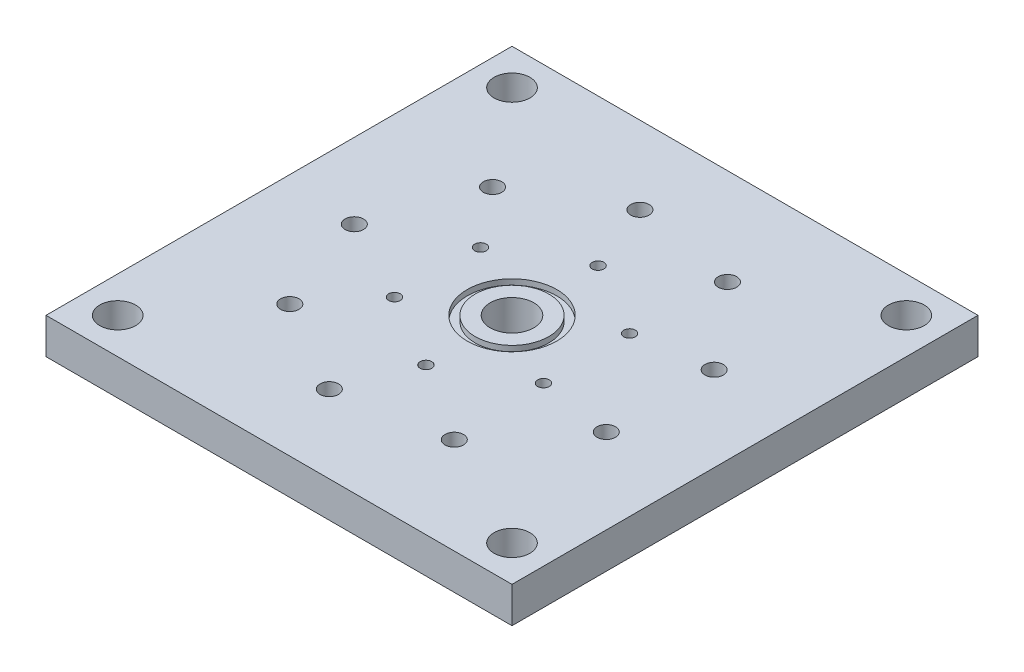
SolidWorks part; units mm, degrees
ref_plane "Front Plane" through (0, 0, 0) normal (0, 0, 1) x (1, 0, 0)
ref_plane "Top Plane" through (0, 0, 0) normal (0, 1, 0) x (1, 0, 0)
ref_plane "Right Plane" through (0, 0, 0) normal (1, 0, 0) x (0, 0, -1)
sketch "Sketch1" plane through (0, 0, 0) normal (0, 1, 0) x (1, 0, 0)
  line L1 (-41.275, -41.275) -> (41.275, -41.275)
  line L2 (-41.275, -41.275) -> (-41.275, 41.275)
  line L3 (-41.275, 41.275) -> (41.275, 41.275)
  line L4 (41.275, -41.275) -> (41.275, 41.275)
  line L5 (-41.275, -41.275) -> (41.275, 41.275) construction
  line L6 (-41.275, 41.275) -> (41.275, -41.275) construction
  point P0 (0, 0)
  dimension "D1" = 82.55
  dimension "D2" = 82.55
extrude "Boss-Extrude1" add sketch "Sketch1" along normal blind 6.35
sketch "Sketch2" plane through (0, 6.35, 0) normal (0, 1, 0) x (1, 0, 0)
  circle A0 centre (0, 0) radius 3.8608
  dimension "D1" = 7.7216
extrude "Cut-Extrude1" cut sketch "Sketch2" against normal up to next
sketch "Sketch4" plane through (0, 6.35, 0) normal (0, 1, 0) x (1, 0, 0)
  circle A0 centre (0, 0) radius 6.5278
  circle A1 centre (0, 0) radius 7.9248
  dimension "D1" = 1.397
extrude "Cut-Extrude3" cut sketch "Sketch4" against normal blind 0.9779
sketch "Sketch5" plane through (0, 6.35, 0) normal (0, 1, 0) x (1, 0, 0)
  circle A0 centre (0, 0) radius 15.24 construction
  circle A1 centre (0, -15.24) radius 1.0325
extrude "Cut-Extrude4" cut sketch "Sketch5" against normal blind 3.175
pattern_circular "CirPattern1" count 6 over 360 about axis through (0, 0, 0) along (0, 1, 0) of "Cut-Extrude4"
sketch "Sketch6" plane through (0, 6.35, 0) normal (0, 1, 0) x (1, 0, 0)
  line L0 (0, 0) -> (13.97, -24.1967) construction
  circle A0 centre (0, 0) radius 27.94 construction
  circle A1 centre (13.97, -24.1967) radius 1.632
extrude "Cut-Extrude5" cut sketch "Sketch6" against normal up to next
pattern_circular "CirPattern2" count 9 over 360 about axis through (0, 0, 0) along (0, 1, 0) of "Cut-Extrude5"
sketch "Sketch7" plane through (0, 6.35, 0) normal (0, 1, 0) x (1, 0, 0)
  line L0 (41.275, 41.275) -> (-41.275, 41.275) construction
  line L1 (41.275, -41.275) -> (41.275, 41.275) construction
  line L2 (0, 0) -> (41.275, 0) construction
  line L3 (0, 0) -> (0, 41.275) construction
  circle A0 centre (34.925, 34.925) radius 3.175
  circle A1 centre (0, 0) radius 38.1 construction
  circle A2 centre (34.925, -34.925) radius 3.175
  circle A3 centre (-34.925, -34.925) radius 3.175
  circle A4 centre (-34.925, 34.925) radius 3.175
  circle A5 centre (34.925, 34.925) radius 5.5562 construction
  dimension "D1" = 6.35
  dimension "D2" = 6.35
extrude "Cut-Extrude6" cut sketch "Sketch7" against normal up to next
equation "\"AnnulusPlateThickness\"= 0.25"
equation "\"D1@Boss-Extrude1\"=\"AnnulusPlateThickness\""
equation "\"AnnulusRadius\"= 0.152"
equation "\"D1@Sketch2\"=\"AnnulusRadius\"*2"
